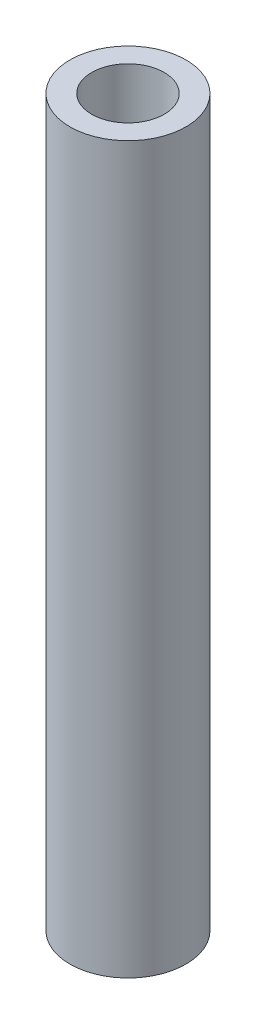
SolidWorks part; units mm, degrees
ref_plane "Front Plane" through (0, 0, 0) normal (0, 0, 1) x (1, 0, 0)
ref_plane "Top Plane" through (0, 0, 0) normal (0, 1, 0) x (1, 0, 0)
ref_plane "Right Plane" through (0, 0, 0) normal (1, 0, 0) x (0, 0, -1)
sketch "Sketch1" plane through (0, 0, 0) normal (0, 1, 0) x (1, 0, 0)
  circle A0 centre (0, 0) radius 1.6
  circle A1 centre (0, 0) radius 1
  dimension "D1" = 3.2
  dimension "D2" = 2
extrude "Boss-Extrude1" add sketch "Sketch1" along normal blind 20
